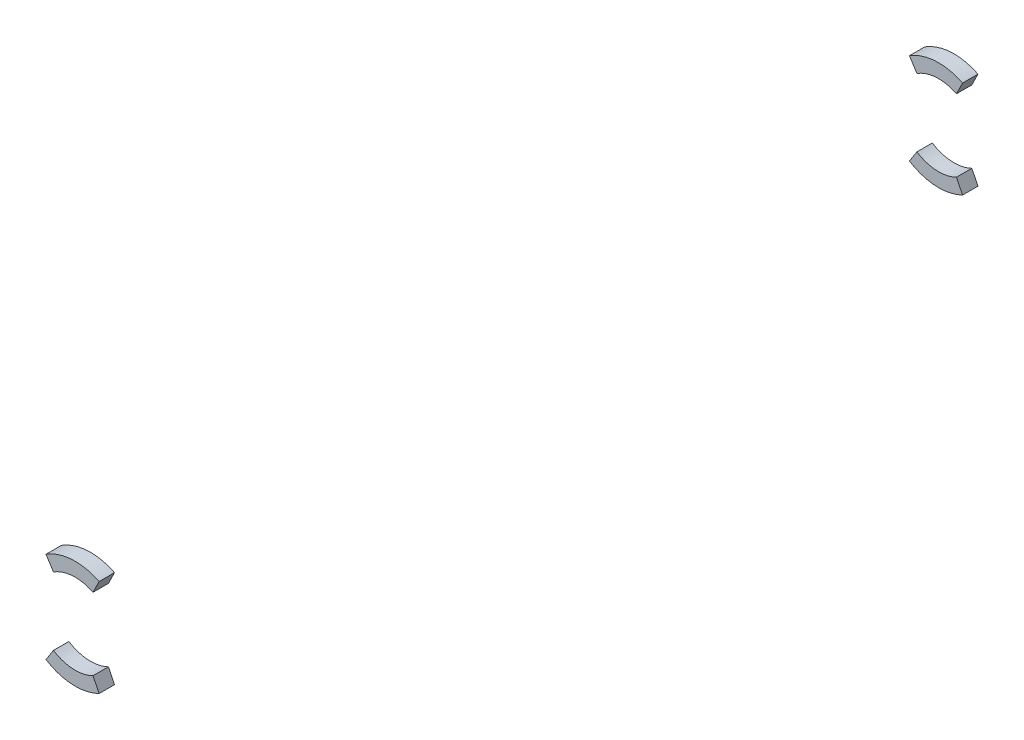
SolidWorks part; units mm, degrees
material "1023 Carbon Steel Sheet (SS)"
ref_plane "Front Plane" through (0, 0, 0) normal (0, 0, 1) x (1, 0, 0)
ref_plane "Top Plane" through (0, 0, 0) normal (0, 1, 0) x (1, 0, 0)
ref_plane "Right Plane" through (0, 0, 0) normal (1, 0, 0) x (0, 0, -1)
sketch "Sketch1" plane through (0, 0, 0) normal (0, 0, 1) x (1, 0, 0)
  circle A0 centre (0, 0) radius 90
  dimension "D1" = 180
extrude "Boss-Extrude1" [suppressed] add sketch "Sketch1" along normal blind 1200
sketch "Sketch2" plane through (0, 0, 0) normal (0, 0, 1) x (1, 0, 0)
  line L0 (-37.8215, 59.139) -> (0, 0) construction
  line L1 (0, 0) -> (31.1075, 62.9302) construction
  line L2 (-37.8215, 59.139) -> (-28.1601, 44.0322)
  line L3 (31.1075, 62.9302) -> (23.1612, 46.8549)
  line L4 (0, 0) -> (144.0107, 0) construction
  line L5 (31.1075, -62.9302) -> (23.1612, -46.8549)
  line L6 (-37.8215, -59.139) -> (-28.1601, -44.0322)
  arc A0 (-37.8215, 59.139) -> (31.1075, 62.9302) centre (0, 0) cw
  arc A1 (-28.1601, 44.0322) -> (23.1612, 46.8549) centre (0, 0) cw
  arc A2 (-37.8215, -59.139) -> (31.1075, -62.9302) centre (0, 0) ccw
  arc A3 (-28.1601, -44.0322) -> (23.1612, -46.8549) centre (0, 0) ccw
extrude "Boss-Extrude2" add sketch "Sketch2" against normal blind 20 separate body
pattern_linear "LPattern1" count 2 spacing 1120 along (0, 0, 1) of "Boss-Extrude2"
